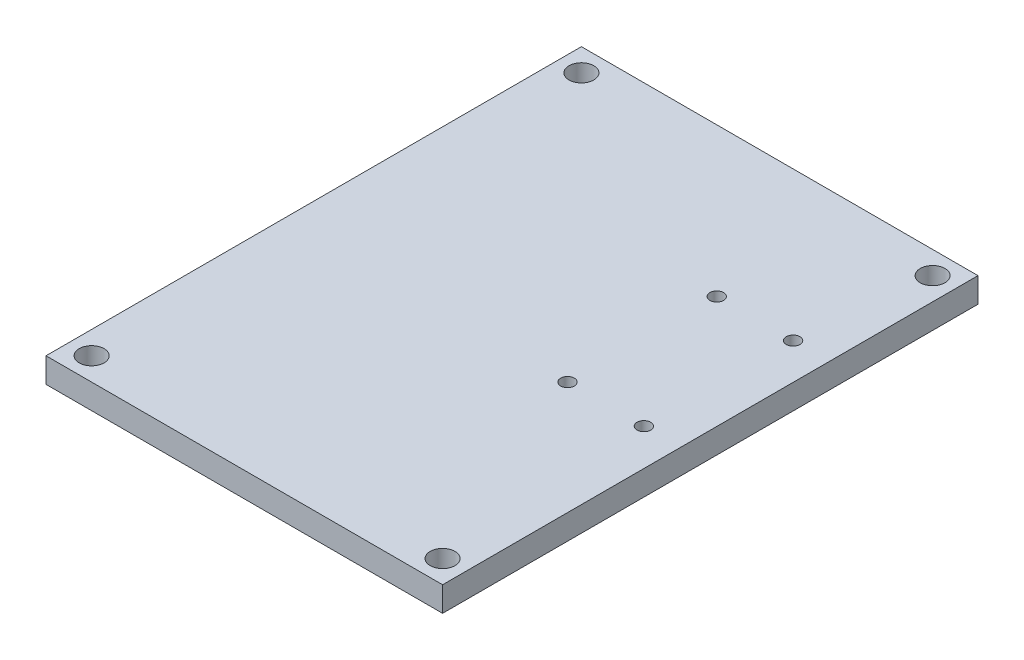
SolidWorks part; units mm, degrees
ref_plane "Front Plane" through (0, 0, 0) normal (0, 0, 1) x (1, 0, 0)
ref_plane "Top Plane" through (0, 0, 0) normal (0, 1, 0) x (1, 0, 0)
ref_plane "Right Plane" through (0, 0, 0) normal (1, 0, 0) x (0, 0, -1)
sketch "Sketch1" plane through (0, 0, 0) normal (0, 1, 0) x (1, 0, 0)
  line L0 (39.37, -58.42) -> (39.37, 58.42) construction
  line L1 (-50.8, -68.58) -> (50.8, -68.58)
  line L2 (-50.8, -68.58) -> (-50.8, 68.58)
  line L3 (-50.8, 68.58) -> (50.8, 68.58)
  line L4 (50.8, -68.58) -> (50.8, 68.58)
  line L5 (-50.8, -68.58) -> (50.8, 68.58) construction
  line L6 (-50.8, 68.58) -> (50.8, -68.58) construction
  line L7 (39.37, 58.42) -> (-39.37, 58.42) construction
  line L8 (-39.37, 58.42) -> (-39.37, -58.42) construction
  line L9 (-39.37, -58.42) -> (39.37, -58.42) construction
  line L10 (-39.37, 58.42) -> (-33.6226, 52.6726) construction
  line L11 (39.37, 58.42) -> (33.6226, 52.6726) construction
  line L12 (-39.37, -58.42) -> (-33.6226, -52.6726) construction
  line L13 (39.37, -58.42) -> (33.6226, -52.6726) construction
  circle A0 centre (-33.6226, 52.6726) radius 3.175
  circle A1 centre (33.6226, 52.6726) radius 3.175
  circle A2 centre (-33.6226, -52.6726) radius 3.175
  circle A3 centre (33.6226, -52.6726) radius 3.175
  point P0 (0, 0)
  dimension "D8" = 6.35
  dimension "D10" = 6.35
  dimension "D12" = 6.35
  dimension "D13" = 6.35
  dimension "D1" = 101.6
  dimension "D2" = 137.16
  dimension "D3" = 78.74
  dimension "D4" = 116.84
  dimension "D5" = 58.42
  dimension "D6" = 39.37
  dimension "D7" = 8.128
  dimension "D9" = 8.128
  dimension "D11" = 8.128
extrude "Boss-Extrude2" add sketch "Sketch1" along normal blind 6.35 contours L2 L1 L4 L3
sketch "Sketch2" plane through (0, 6.35, 0) normal (0, 1, 0) x (1, 0, 0)
  line L0 (30.0355, 48.26) -> (30.0355, -48.26) construction
  line L1 (30.0355, -48.26) -> (-29.972, -48.26) construction
  line L2 (-29.972, -48.26) -> (-29.972, 48.26) construction
  line L3 (-29.972, 48.26) -> (30.0355, 48.26) construction
  line L4 (-50.8, 68.58) -> (-44.9888, 62.7688) construction
  line L5 (50.8, 68.58) -> (44.9837, 62.7637) construction
  line L6 (-29.972, -48.26) -> (-44.9514, -62.7314) construction
  line L7 (50.8, -68.58) -> (44.9837, -62.7637) construction
  line L8 (-50.8, -68.58) -> (-44.9514, -62.7314) construction
  line L9 (-50.8, -68.58) -> (-50.8, 68.58) construction
  line L10 (30.0355, 48.26) -> (44.9837, 62.7637) construction
  line L11 (50.8, -68.58) -> (50.8, 68.58) construction
  line L12 (-50.8, -68.58) -> (50.8, -68.58) construction
  circle A0 centre (-44.9888, 62.7688) radius 3.175
  circle A1 centre (44.9837, 62.7637) radius 3.175
  circle A2 centre (-44.9514, -62.7314) radius 3.175
  circle A3 centre (44.9837, -62.7637) radius 3.175
  dimension "D6" = 6.35
  dimension "D7" = 6.35
  dimension "D8" = 6.35
  dimension "D9" = 6.35
  dimension "D11" = 20.828
  dimension "D1" = 60.0075
  dimension "D2" = 96.52
  dimension "D3" = 48.26
  dimension "D4" = 29.972
  dimension "D5" = 45
  dimension "D10" = 45
  dimension "D12" = 45
  dimension "D13" = 20.8808
  dimension "D14" = 45
  dimension "D15" = 20.828
  dimension "D16" = 20.828
extrude "Cut-Extrude1" cut sketch "Sketch2" against normal blind 6.35
sketch "Sketch3" plane through (0, 6.35, 0) normal (0, 1, 0) x (1, 0, 0)
  line L1 (-50.8, 68.58) -> (50.8, 68.58) construction
  line L2 (50.8, -68.58) -> (50.8, 68.58) construction
  circle A0 centre (21.971, 30.48) radius 1.7526
  circle A1 centre (41.529, 30.48) radius 1.7526
  circle A2 centre (21.844, -7.62) radius 1.7526
  circle A3 centre (41.402, -7.62) radius 1.7526
  dimension "D1" = 3.5052
  dimension "D2" = 19.558
  dimension "D4" = 3.5052
  dimension "D5" = 38.1
  dimension "D6" = 9.271
  dimension "D7" = 3.5052
  dimension "D8" = 19.558
  dimension "D9" = 38.1
  dimension "D10" = 3.5052
  dimension "D3" = 38.1
  dimension "D11" = 38.1
  dimension "D12" = 9.398
extrude "Cut-Extrude2" cut sketch "Sketch3" against normal blind 6.35
